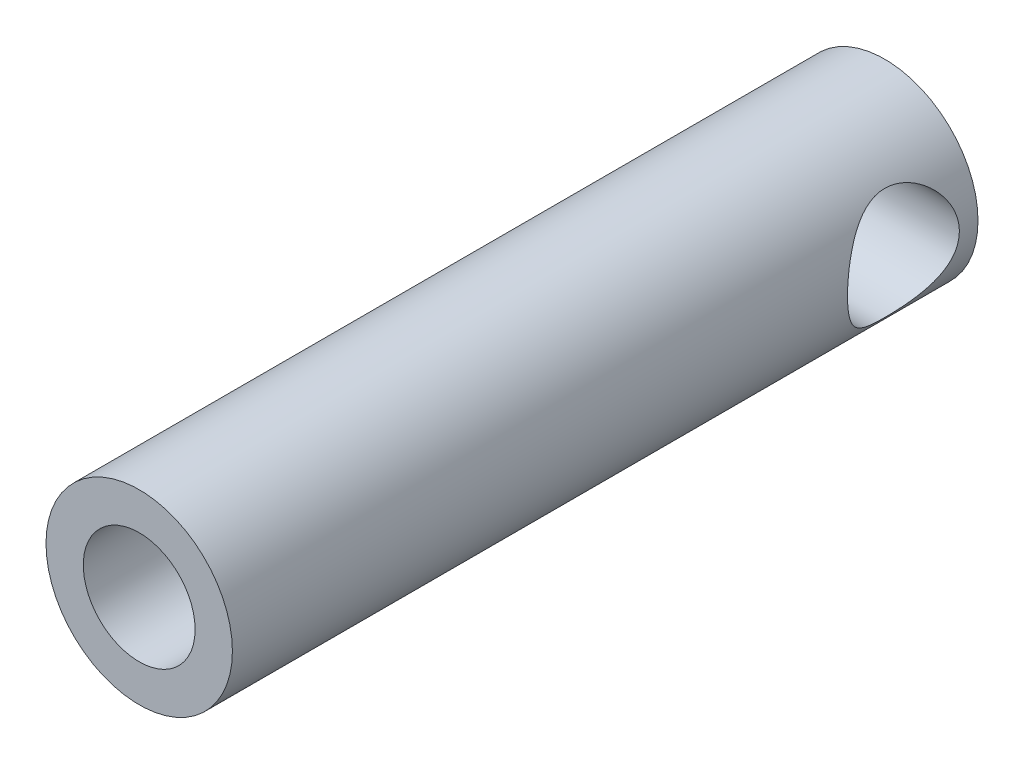
SolidWorks part; units mm, degrees
ref_plane "Front Plane" through (0, 0, 0) normal (0, 0, 1) x (1, 0, 0)
ref_plane "Top Plane" through (0, 0, 0) normal (0, 1, 0) x (1, 0, 0)
ref_plane "Right Plane" through (0, 0, 0) normal (1, 0, 0) x (0, 0, -1)
sketch "Sketch1" plane through (0, 0, 0) normal (0, 0, 1) x (1, 0, 0)
  circle A0 centre (0, 0) radius 3.175
  dimension "D1" = 6.35
extrude "Boss-Extrude1" add sketch "Sketch1" along normal blind 25.4
sketch "Sketch2" plane through (0, 0, 25.4) normal (0, 0, 1) x (1, 0, 0)
  circle A0 centre (0, 0) radius 1.905
  dimension "D1" = 3.81
extrude "Cut-Extrude1" cut sketch "Sketch2" against normal blind 12.7
sketch "Sketch3" plane through (0, 0, 0) normal (1, 0, 0) x (0, 0, -1)
  circle A0 centre (-2.54, 0) radius 1.905
  point P2 (0, 0)
  dimension "D2" = 3.81
  dimension "D1" = 2.54
extrude "Cut-Extrude2" cut sketch "Sketch3" against normal through all and the other way through all
